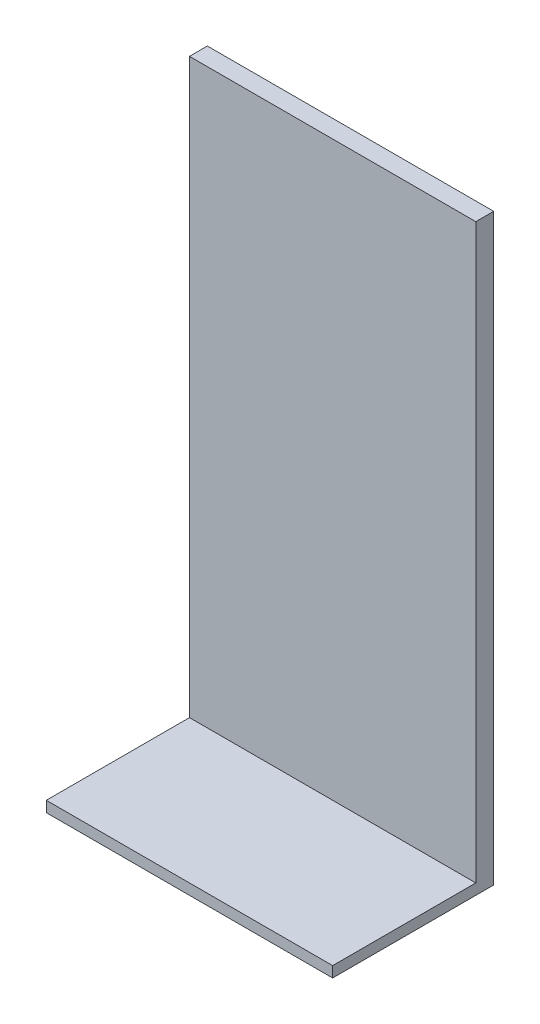
SolidWorks part; units mm, degrees
ref_plane "Front Plane" through (0, 0, 0) normal (0, 0, 1) x (1, 0, 0)
ref_plane "Top Plane" through (0, 0, 0) normal (0, 1, 0) x (1, 0, 0)
ref_plane "Right Plane" through (0, 0, 0) normal (1, 0, 0) x (0, 0, -1)
sketch "Sketch1" plane through (0, 0, 0) normal (1, 0, 0) x (0, 0, -1)
  line L0 (0, 0) -> (-45, 0)
  line L1 (-45, 0) -> (-45, 3)
  line L2 (-45, 3) -> (-5, 3)
  line L3 (-5, 3) -> (-5, 163)
  line L4 (-5, 163) -> (0, 163)
  line L5 (0, 163) -> (0, 0)
  dimension "D1" = 3
  dimension "D2" = 45
  dimension "D3" = 5
  dimension "D4" = 163
extrude "Boss-Extrude1" add sketch "Sketch1" along normal blind 80
